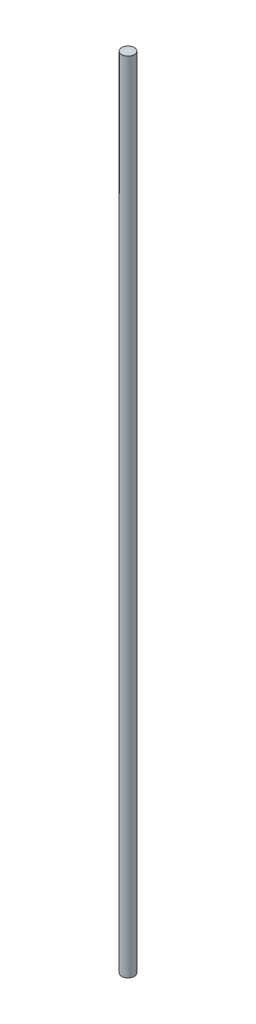
SolidWorks part; units mm, degrees
ref_plane "Front Plane" through (0, 0, 0) normal (0, 0, 1) x (1, 0, 0)
ref_plane "Top Plane" through (0, 0, 0) normal (0, 1, 0) x (1, 0, 0)
ref_plane "Right Plane" through (0, 0, 0) normal (1, 0, 0) x (0, 0, -1)
sketch "Sketch1" plane through (0, 0, 0) normal (0, 1, 0) x (1, 0, 0)
  circle A0 centre (0, 0) radius 4
  dimension "D1" = 8
extrude "Boss-Extrude1" add sketch "Sketch1" along normal blind 510
